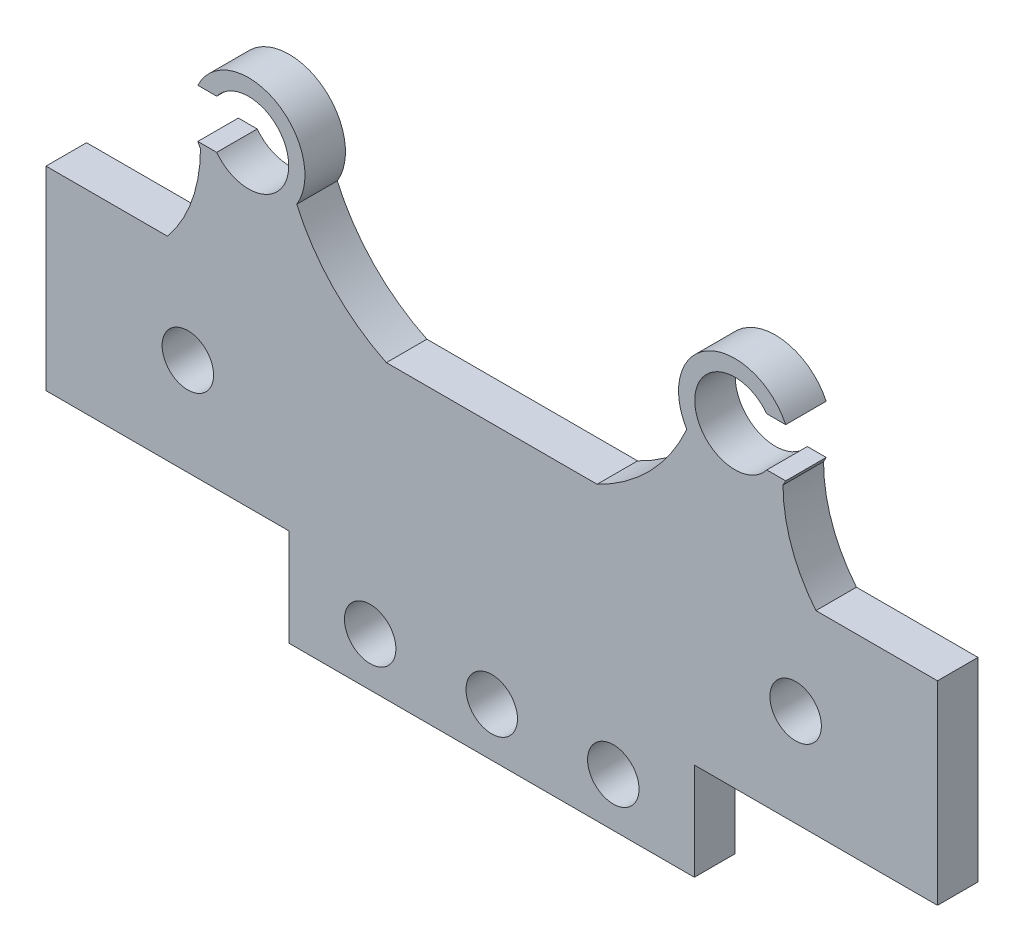
SolidWorks part; units mm, degrees
ref_plane "Alzado" through (0, 0, 0) normal (0, 0, 1) x (1, 0, 0)
ref_plane "Planta" through (0, 0, 0) normal (0, 1, 0) x (1, 0, 0)
ref_plane "Vista lateral" through (0, 0, 0) normal (1, 0, 0) x (0, 0, -1)
sketch "Croquis1" plane through (0, 0, 0) normal (0, 0, 1) x (1, 0, 0)
  line L0 (13, 0) -> (-13, 0)
  line L1 (-55, 0) -> (-55, -24)
  line L2 (-55, -24) -> (-25, -24)
  line L3 (-25, -24) -> (-25, -36)
  line L4 (-25, -36) -> (25, -36)
  line L5 (0, -36) -> (0, 0) construction
  line L6 (-40, 0) -> (-55, 0)
  line L7 (40, 0) -> (55, 0)
  line L8 (55, 0) -> (55, -24)
  line L9 (25, -24) -> (25, -36)
  line L10 (55, -24) -> (25, -24)
  circle A0 centre (-30, 15) radius 4.95
  arc A2 (-24.0615, 11.3894) -> (-35.9385, 11.3894) centre (-30, 15) ccw
  arc A3 (-35.9385, 11.3894) -> (-40, 0) centre (-53.9385, 11.3894) cw
  arc A4 (-24.0615, 11.3894) -> (-13, 0) centre (-3.0454, 20.7342) ccw
  circle A5 centre (-30, 15) radius 6.95 construction
  circle A7 centre (-37.5, -12) radius 3.175
  circle A8 centre (0, -30) radius 3.175
  arc A9 (24.0615, 11.3894) -> (13, 0) centre (3.0454, 20.7342) cw
  circle A10 centre (30, 15) radius 4.95
  arc A11 (24.0615, 11.3894) -> (35.9385, 11.3894) centre (30, 15) cw
  arc A12 (35.9385, 11.3894) -> (40, 0) centre (53.9385, 11.3894) ccw
  circle A13 centre (37.5, -12) radius 3.175
  circle A14 centre (-15, -30) radius 3.175
  circle A15 centre (15, -30) radius 3.175
  dimension "D2" = 9.9
  dimension "D3" = 15
  dimension "D5" = 18
  dimension "D6" = 15
  dimension "D8" = 23
  dimension "D15" = 37.5
  dimension "D14" = 6.35
  dimension "D1" = 2
  dimension "D4" = 30
  dimension "D7" = 55
  dimension "D9" = 13
  dimension "D10" = 24
  dimension "D11" = 30
  dimension "D12" = 12
  dimension "D13" = 12
  dimension "D16" = 30
  dimension "D17" = 10
extrude "Saliente-Extruir1" add sketch "Croquis1" along normal blind 5
sketch "Croquis2" plane through (0, 0, 0) normal (0, 0, 1) x (1, 0, 0)
  line L0 (-30, 15) -> (-36.95, 15) construction
  line L1 (-30, 18) -> (-36.2692, 18)
  line L2 (-30, 12) -> (-36.2692, 12)
  line L3 (-30, 12) -> (-36.95, 12) construction
  line L4 (-30, 18) -> (-36.95, 18) construction
  line L5 (-30, 18) -> (-30, 12)
  line L6 (0, 0) -> (0, -26.825) construction
  line L7 (30, 18) -> (30, 12)
  line L8 (30, 12) -> (36.2692, 12)
  line L9 (30, 18) -> (36.2692, 18)
  arc A0 (-24.0615, 11.3894) -> (-35.9385, 11.3894) centre (-30, 15) ccw construction
  arc A1 (-36.2692, 18) -> (-36.2692, 12) centre (-30, 15) ccw
  circle A2 centre (0, -30) radius 3.175 construction
  arc A3 (36.2692, 18) -> (36.2692, 12) centre (30, 15) cw
  dimension "D1" = 3
  dimension "D2" = 3
extrude "Cortar-Extruir1" cut sketch "Croquis2" along normal through all
